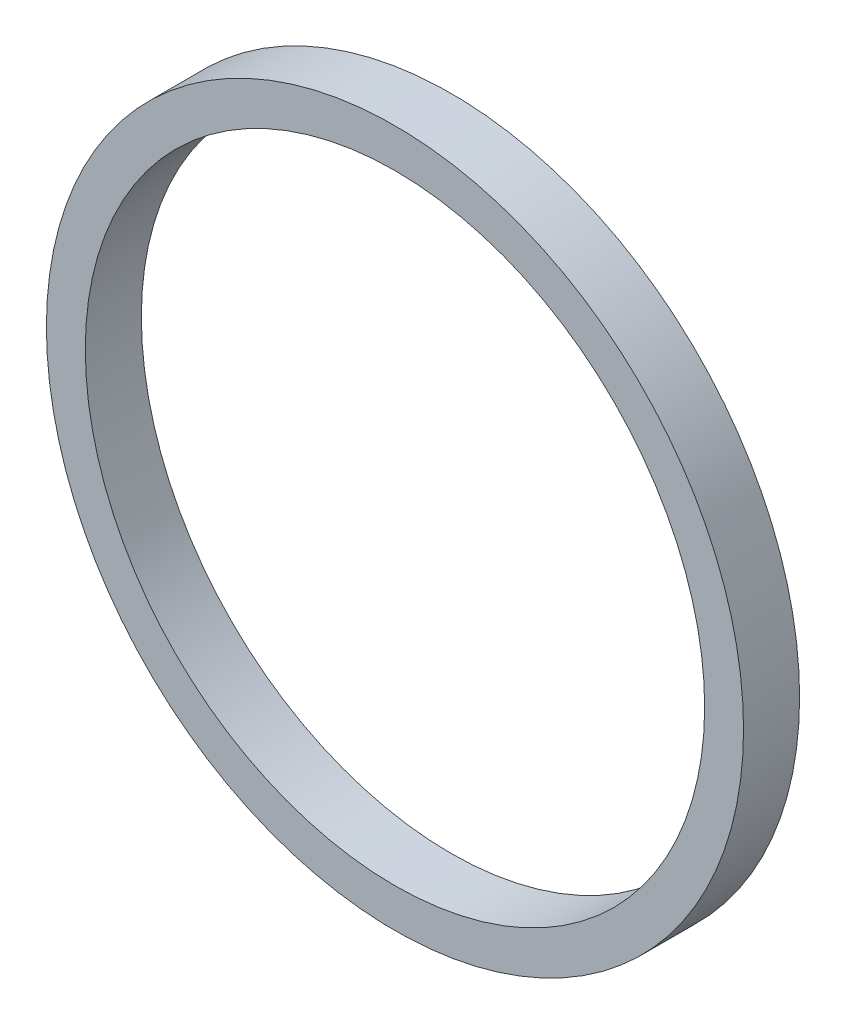
SolidWorks part; units mm, degrees
material "ABS"
ref_plane "Front Plane" through (0, 0, 0) normal (0, 0, 1) x (1, 0, 0)
ref_plane "Top Plane" through (0, 0, 0) normal (0, 1, 0) x (1, 0, 0)
ref_plane "Right Plane" through (0, 0, 0) normal (1, 0, 0) x (0, 0, -1)
sketch "Sketch2" plane through (0, 0, 0) normal (0, 0, 1) x (1, 0, 0)
  circle A0 centre (0, 0) radius 22.1
  circle A1 centre (0, 0) radius 24.875
  dimension "D1" = 49.75
  dimension "D2" = 44.2
extrude "Boss-Extrude1" add sketch "Sketch2" along normal blind 4
